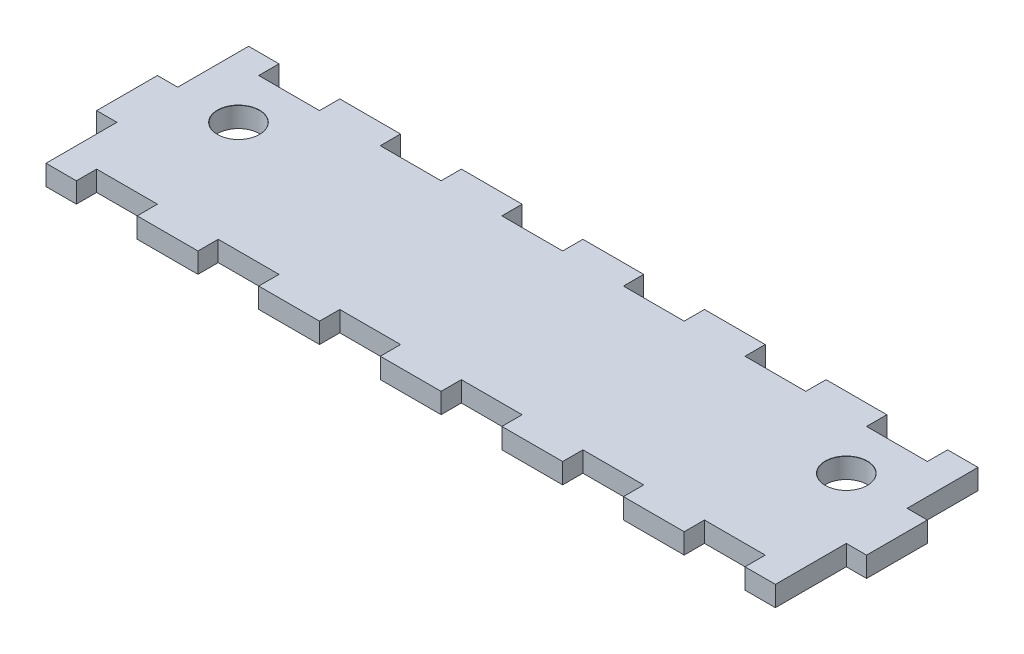
SolidWorks part; units mm, degrees
ref_plane "Front Plane" through (0, 0, 0) normal (0, 0, 1) x (1, 0, 0)
ref_plane "Top Plane" through (0, 0, 0) normal (0, 1, 0) x (1, 0, 0)
ref_plane "Right Plane" through (0, 0, 0) normal (1, 0, 0) x (0, 0, -1)
sketch "Sketch1" plane through (0, 0, 0) normal (0, 1, 0) x (1, 0, 0)
  line L64 (54, 15) -> (49.5, 15)
  line L65 (49.5, 15) -> (49.5, 12)
  line L66 (49.5, 12) -> (40.5, 12)
  line L67 (40.5, 12) -> (40.5, 15)
  line L68 (40.5, 15) -> (31.5, 15)
  line L69 (31.5, 15) -> (31.5, 12)
  line L70 (31.5, 12) -> (22.5, 12)
  line L71 (22.5, 12) -> (22.5, 15)
  line L72 (22.5, 15) -> (13.5, 15)
  line L73 (13.5, 15) -> (13.5, 12)
  line L74 (13.5, 12) -> (4.5, 12)
  line L75 (4.5, 12) -> (4.5, 15)
  line L76 (4.5, 15) -> (-4.5, 15)
  line L77 (-4.5, 15) -> (-4.5, 12)
  line L78 (-4.5, 12) -> (-13.5, 12)
  line L79 (-13.5, 12) -> (-13.5, 15)
  line L80 (-13.5, 15) -> (-22.5, 15)
  line L81 (-22.5, 15) -> (-22.5, 12)
  line L82 (-22.5, 12) -> (-31.5, 12)
  line L83 (-31.5, 12) -> (-31.5, 15)
  line L84 (-31.5, 15) -> (-40.5, 15)
  line L85 (-40.5, 15) -> (-40.5, 12)
  line L86 (-40.5, 12) -> (-49.5, 12)
  line L87 (-49.5, 12) -> (-49.5, 15)
  line L88 (-49.5, 15) -> (-54, 15)
  line L89 (-54, 15) -> (-54, 12)
  line L90 (-54, 12) -> (-54, 4.5)
  line L91 (-54, 4.5) -> (-57, 4.5)
  line L92 (-57, 4.5) -> (-57, -4.5)
  line L93 (-57, -4.5) -> (-54, -4.5)
  line L94 (-54, -4.5) -> (-54, -12)
  line L95 (-54, -12) -> (-54, -15)
  line L96 (-54, -15) -> (-49.5, -15)
  line L97 (-49.5, -15) -> (-49.5, -12)
  line L98 (-49.5, -12) -> (-40.5, -12)
  line L99 (-40.5, -12) -> (-40.5, -15)
  line L100 (-40.5, -15) -> (-31.5, -15)
  line L101 (-31.5, -15) -> (-31.5, -12)
  line L102 (-31.5, -12) -> (-22.5, -12)
  line L103 (-22.5, -12) -> (-22.5, -15)
  line L104 (-22.5, -15) -> (-13.5, -15)
  line L105 (-13.5, -15) -> (-13.5, -12)
  line L106 (-13.5, -12) -> (-4.5, -12)
  line L107 (-4.5, -12) -> (-4.5, -15)
  line L108 (-4.5, -15) -> (4.5, -15)
  line L109 (4.5, -15) -> (4.5, -12)
  line L110 (4.5, -12) -> (13.5, -12)
  line L111 (13.5, -12) -> (13.5, -15)
  line L112 (13.5, -15) -> (22.5, -15)
  line L113 (22.5, -15) -> (22.5, -12)
  line L114 (22.5, -12) -> (31.5, -12)
  line L115 (31.5, -12) -> (31.5, -15)
  line L116 (31.5, -15) -> (40.5, -15)
  line L117 (40.5, -15) -> (40.5, -12)
  line L118 (40.5, -12) -> (49.5, -12)
  line L119 (49.5, -12) -> (49.5, -15)
  line L120 (49.5, -15) -> (54, -15)
  line L121 (54, -15) -> (54, -12)
  line L122 (54, -12) -> (54, -4.5)
  line L123 (54, -4.5) -> (57, -4.5)
  line L124 (57, -4.5) -> (57, 4.5)
  line L125 (57, 4.5) -> (54, 4.5)
  line L126 (54, 4.5) -> (54, 12)
  line L127 (54, 12) -> (54, 15)
  line L128 (-57, 4.5) -> (-57, 15) construction
  line L129 (-57, 15) -> (-54, 15) construction
  line L130 (57, -4.5) -> (57, -15) construction
  line L131 (57, -15) -> (54, -15) construction
  line L132 (-57, 15) -> (57, -15) construction
  point P64 (0, 0)
extrude "Boss-Extrude1" add sketch "Sketch1" along normal mid plane 3
sketch "Sketch2" plane through (0, 1.5, 0) normal (0, 1, 0) x (1, 0, 0)
  text T0 "Front/Back\r\n"
extrude "Cut-Extrude1" [suppressed] cut sketch "Sketch2" against normal blind 1
sketch "Sketch3" plane through (0, 1.5, 0) normal (0, 1, 0) x (1, 0, 0)
  line L0 (-45, 4.5) -> (45, 4.5) construction
  line L1 (-57, 4.5) -> (-57, -4.5) construction
  line L2 (57, -4.5) -> (57, 4.5) construction
  line L3 (13.5, -15) -> (22.5, -15) construction
  point P0 (-45, 4.5)
  point P1 (45, 4.5)
  dimension "D1" = 12
  dimension "D2" = 12
  dimension "D3" = 19.5
hole_wizard "Ø6.2 (6.2) Diameter Hole1" positions "Sketch3" profile "Sketch4" hole size "Ø6.2" standard "ISO" end condition through all
sketch "Sketch4" plane through (-45, 1.5, -4.5) normal (1, 0, 0) x (0, 0, 1)
  line L0 (0, 0) -> (0, 3)
  line L1 (0, 3) -> (3.1, 3)
  line L2 (3.1, 3) -> (3.1, 0.025)
  line L3 (3.1, 0.025) -> (3.125, 0)
  line L5 (3.125, 0) -> (0, 0)
  line L6 (-3.1, 0.025) -> (-3.125, 0) construction
  line L11 (0, -6.35) -> (0, 107.95) construction
  dimension "Thru Hole Dia." = 6.2
  dimension "Thru Hole Depth" = 3
  dimension "Near C'Sink Dia." = 6.25
  dimension "Near C'Sink Angle" = 90
